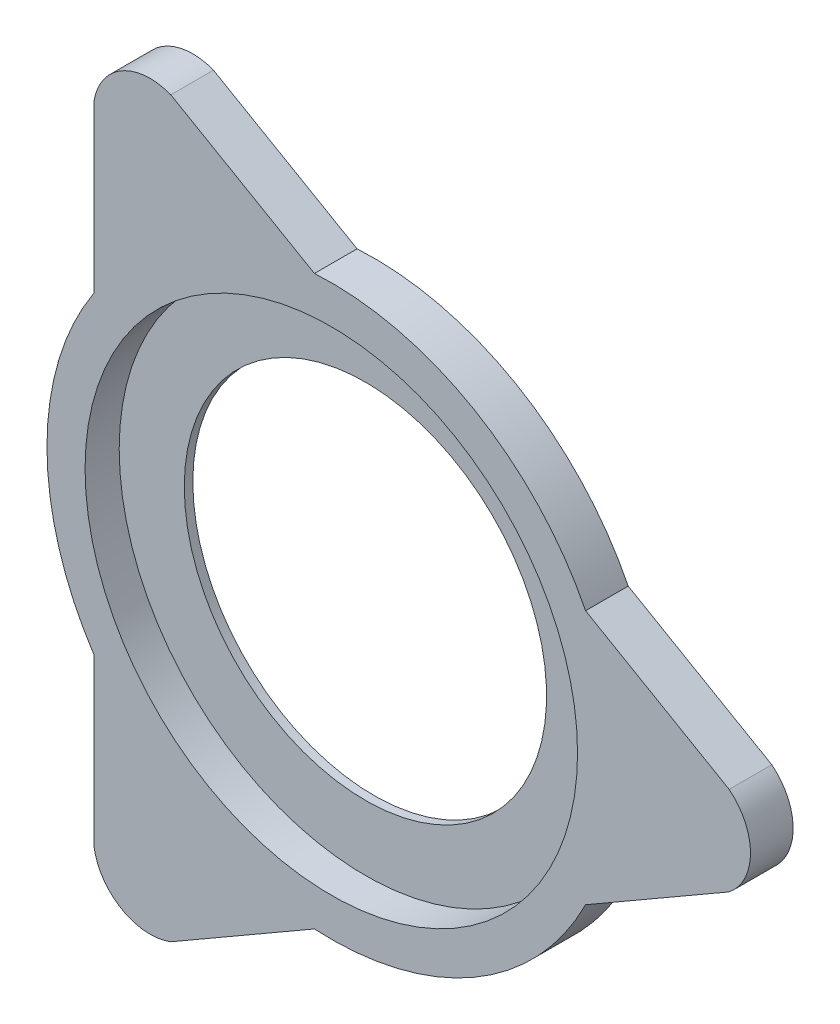
SolidWorks part; units mm, degrees
ref_plane "Front" through (0, 0, 0) normal (0, 0, 1) x (1, 0, 0)
ref_plane "Top" through (0, 0, 0) normal (0, 1, 0) x (1, 0, 0)
ref_plane "Right" through (0, 0, 0) normal (1, 0, 0) x (0, 0, -1)
other "Configuration Table"
sketch "Sketch1" plane through (0, 0, 0) normal (0, 0, 1) x (1, 0, 0)
  line L0 (88.8452, -9.918) -> (56.7796, -28.4311)
  line L1 (80.9128, 0) -> (-40.4564, 70.0725) construction
  line L2 (-40.4564, 70.0725) -> (-40.4564, -70.0725) construction
  line L3 (-40.4564, -70.0725) -> (80.9128, 0) construction
  line L4 (88.8452, 9.918) -> (56.7796, 28.4311)
  line L5 (-53.0118, 71.9832) -> (-53.0118, 34.957)
  line L6 (-3.7678, -63.3881) -> (-35.8334, -81.9012)
  line L7 (-53.0118, -34.957) -> (-53.0118, -71.9832)
  line L8 (-3.7678, 63.3881) -> (-35.8334, 81.9012)
  arc A0 (56.7796, 28.4311) -> (-3.7678, 63.3881) centre (0, 0) ccw
  circle A1 centre (0, 0) radius 40.4564
  arc A2 (-53.0118, 71.9832) -> (-35.8334, 81.9012) centre (-40.4564, 70.0725) cw
  arc A3 (88.8452, 9.918) -> (88.8452, -9.918) centre (80.9128, 0) cw
  arc A4 (-35.8334, -81.9012) -> (-53.0118, -71.9832) centre (-40.4564, -70.0725) cw
  arc A5 (-53.0118, 34.957) -> (-53.0118, -34.957) centre (0, 0) ccw
  arc A6 (-3.7678, -63.3881) -> (56.7796, -28.4311) centre (0, 0) ccw
  dimension "D1" = 63.5
  dimension "D3" = 12.7
extrude "Base-Extrude" add sketch "Sketch1" along normal blind 9.525
sketch "Sketch2" plane through (0, 0, 9.525) normal (0, 0, 1) x (1, 0, 0)
  circle A0 centre (0, 0) radius 54.9919
  arc A1 (56.7796, 28.4311) -> (-3.7678, 63.3881) centre (0, 0) ccw construction
extrude "Cut-Extrude1" cut sketch "Sketch2" against normal blind 7.62
